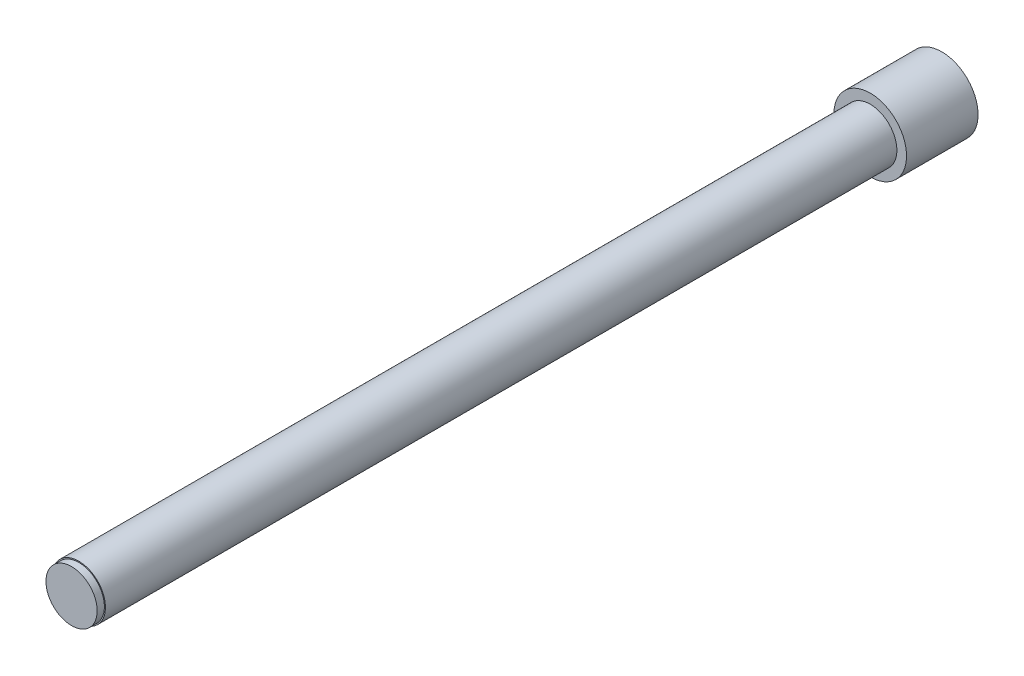
SolidWorks part; units mm, degrees
ref_plane "Front Plane" through (0, 0, 0) normal (0, 0, 1) x (1, 0, 0)
ref_plane "Top Plane" through (0, 0, 0) normal (0, 1, 0) x (1, 0, 0)
ref_plane "Right Plane" through (0, 0, 0) normal (1, 0, 0) x (0, 0, -1)
sketch "Sketch1" plane through (0, 0, 0) normal (0, 0, 1) x (1, 0, 0)
  circle A0 centre (0, 0) radius 2.5
  dimension "D1" = 5
extrude "Boss-Extrude1" add sketch "Sketch1" along normal mid plane 81.534
ref_axis "Axis1" through (0, 0, 40.767) along (0, 0, -1)
sketch "Sketch2" plane through (0, 0, 0) normal (1, 0, 0) x (0, 0, -1)
  line L0 (40.767, 2.5) -> (-40.767, 2.5) construction
  line L1 (-40.7911, 2.5) -> (-40.0911, 2.5)
  line L2 (-40.7911, 2.5) -> (-40.7911, 2.4)
  line L3 (-40.7911, 2.4) -> (-40.0911, 2.4)
  line L4 (-40.0911, 2.5) -> (-40.0911, 2.4)
  line L5 (-40.0911, -68.9968) -> (-40.0911, -63.3921) construction
  dimension "D1" = 0.1
  dimension "D2" = 0.7
revolve "Cut-Revolve1" cut sketch "Sketch2" angle 360 about axis through (0, 0, 40.767) along (0, 0, -1)
sketch "Sketch4" plane through (0, 0, -40.767) normal (0, 0, -1) x (-1, 0, 0)
  circle A0 centre (0, 0) radius 3.4022
extrude "Boss-Extrude2" add sketch "Sketch4" against normal up to surface (6.7019 mm away)
